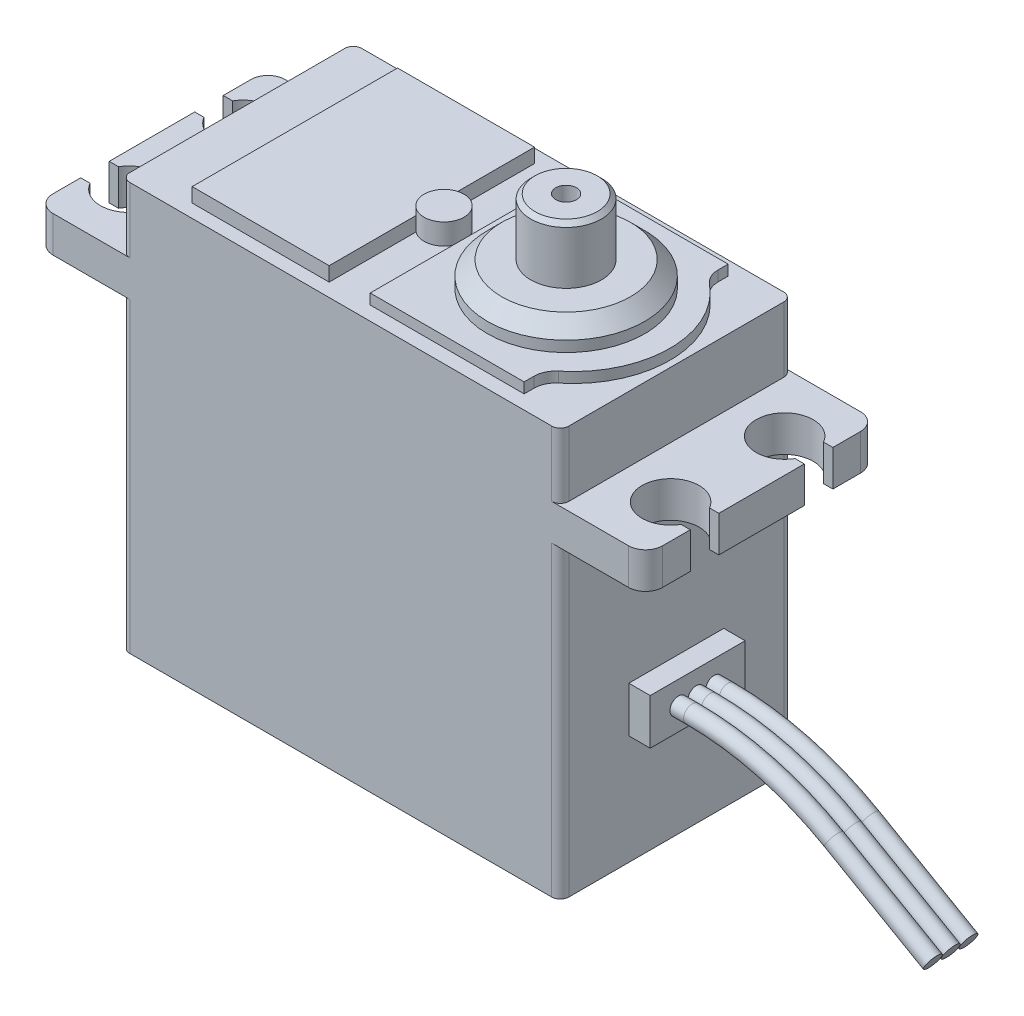
SolidWorks part; units mm, degrees
ref_plane "Front Plane" through (0, 0, 0) normal (0, 0, 1) x (1, 0, 0)
ref_plane "Top Plane" through (0, 0, 0) normal (0, 1, 0) x (1, 0, 0)
ref_plane "Right Plane" through (0, 0, 0) normal (1, 0, 0) x (0, 0, -1)
sketch "Sketch1" plane through (0, 0, 0) normal (0, 1, 0) x (1, 0, 0)
  line L1 (0, 0) -> (30.8, 0)
  line L2 (0, 0) -> (0, 16.28)
  line L3 (0, 16.28) -> (30.8, 16.28)
  line L4 (30.8, 0) -> (30.8, 16.28)
  dimension "D1" = 16.28
  dimension "D2" = 30.8
extrude "Boss-Extrude1" add sketch "Sketch1" along normal blind 28.62
sketch "Sketch3" plane through (0, 0, 0) normal (0, 0, 1) x (1, 0, 0)
  line L0 (0, 21.51) -> (30.8, 21.51) construction
  line L1 (0, 28.62) -> (0, 0) construction
  line L2 (30.8, 28.62) -> (30.8, 0) construction
  line L3 (0, 0) -> (30.8, 0) construction
  line L4 (15.4, 28.62) -> (15.4, 24.7543) construction
  line L5 (30.8, 21.51) -> (36.785, 21.51)
  line L6 (30.8, 21.51) -> (30.8, 24.04)
  line L7 (30.8, 24.04) -> (36.785, 24.04)
  line L8 (36.785, 21.51) -> (36.785, 24.04)
  line L9 (0, 28.62) -> (30.8, 28.62) construction
  line L10 (-5.985, 21.51) -> (-5.985, 24.04)
  line L11 (0, 24.04) -> (-5.985, 24.04)
  line L12 (0, 21.51) -> (0, 24.04)
  line L13 (0, 21.51) -> (-5.985, 21.51)
  dimension "D1" = 21.51
  dimension "D2" = 2.53
  dimension "D3" = 21.385
extrude "Boss-Extrude2" add sketch "Sketch3" against normal up to surface (16.28 mm away) up to face at (15.4, 14.31, -16.28)
sketch "Sketch4" plane through (0, 28.62, 0) normal (0, 1, 0) x (1, 0, 0)
  line L0 (4.04, 8.14) -> (0, 8.14) construction
  line L1 (13.65, 15.345) -> (4.04, 15.345)
  line L2 (13.65, 15.345) -> (13.65, 0.935)
  line L3 (13.65, 0.935) -> (4.04, 0.935)
  line L4 (4.04, 15.345) -> (4.04, 0.935)
  line L5 (0, 16.28) -> (0, 0) construction
  line L6 (30.8, 0) -> (30.8, 16.28) construction
  dimension "D1" = 14.41
  dimension "D2" = 9.61
  dimension "D3" = 26.76
extrude "Boss-Extrude3" add sketch "Sketch4" along normal blind 1
sketch "Sketch5" plane through (0, 28.62, 0) normal (0, 1, 0) x (1, 0, 0)
  line L0 (13.65, 0.935) -> (13.65, 15.345) construction
  line L1 (27.28, 0.985) -> (16.48, 0.985)
  line L2 (27.28, 2.4415) -> (27.28, 13.8385) construction
  line L3 (27.28, 15.295) -> (16.48, 15.295)
  line L4 (16.48, 0.985) -> (16.48, 15.295)
  line L5 (30.36, 8.14) -> (30.8, 8.14) construction
  line L6 (30.8, 0) -> (30.8, 16.28) construction
  line L7 (23.23, 8.14) -> (28.73, 8.14) construction
  line L8 (27.28, 0.985) -> (27.28, 2.4415)
  line L9 (4.04, 15.345) -> (4.04, 0.935) construction
  line L11 (27.28, 13.8385) -> (27.28, 15.295)
  arc A1 (27.28, 2.4415) -> (27.28, 13.8385) centre (23.5484, 8.14) ccw
  dimension "D1" = 2.83
  dimension "D2" = 1.4565
  dimension "D3" = 10.8
  dimension "D5" = 13.88
  dimension "D6" = 24.69
extrude "Boss-Extrude4" add sketch "Sketch5" along normal blind 0.73
sketch "Sketch6" plane through (0, 29.35, 0) normal (0, 1, 0) x (1, 0, 0)
  line L0 (28.59, 8.14) -> (23.07, 8.14) construction
  line L1 (4.04, 15.345) -> (4.04, 0.935) construction
  circle A0 centre (23.07, 8.14) radius 5.52
  dimension "D1" = 11.04
  dimension "D2" = 24.55
extrude "Boss-Extrude5" add sketch "Sketch6" along normal blind 1.75
chamfer "Chamfer1" distance 1 angle 45 1 edges at (23.07, 31.1, -2.62)
fillet "Fillet1" radius 1.5 2 edges at (27.28, 28.985, -13.8385) (27.28, 28.985, -2.4415)
sketch "Sketch7" plane through (0, 28.62, 0) normal (0, 1, 0) x (1, 0, 0)
  circle A0 centre (14.5043, 8.14) radius 1.4
  dimension "D1" = 2.8
extrude "Boss-Extrude6" add sketch "Sketch7" along normal blind 1.47
sketch "Sketch8" plane through (0, 31.1, 0) normal (0, 1, 0) x (1, 0, 0)
  circle A0 centre (23.07, 8.14) radius 2.48
  dimension "D1" = 4.96
extrude "Boss-Extrude7" add sketch "Sketch8" along normal blind 4
sketch "Sketch9" plane through (0, 24.04, 0) normal (0, 1, 0) x (1, 0, 0)
  line L0 (30.8, 8.14) -> (36.785, 8.14) construction
  line L1 (30.8, 16.28) -> (30.8, 0) construction
  line L2 (36.785, 16.28) -> (36.785, 0) construction
  line L3 (15.4, 16.28) -> (15.4, 0) construction
  line L4 (30.8, 16.28) -> (0, 16.28) construction
  line L5 (0, 0) -> (30.8, 0) construction
  line L6 (34.4, 12.14) -> (32.4, 12.14) construction
  line L7 (34.4, 10.14) -> (34.4, 8.14) construction
  line L8 (37.2465, 13.14) -> (37.2465, 11.14)
  line L9 (36.1321, 11.14) -> (37.2465, 11.14)
  line L10 (36.1321, 3.14) -> (37.2465, 3.14)
  line L11 (36.1321, 13.14) -> (37.2465, 13.14)
  line L12 (37.2465, 3.14) -> (37.2465, 5.14)
  line L13 (36.1321, 5.14) -> (37.2465, 5.14)
  line L14 (-3.6, 10.14) -> (-3.6, 8.14) construction
  line L15 (-3.6, 12.14) -> (-1.6, 12.14) construction
  line L16 (0, 8.14) -> (-5.985, 8.14) construction
  line L17 (-5.3321, 5.14) -> (-6.4465, 5.14)
  line L18 (-6.4465, 3.14) -> (-6.4465, 5.14)
  line L19 (-5.3321, 13.14) -> (-6.4465, 13.14)
  line L20 (-5.3321, 3.14) -> (-6.4465, 3.14)
  line L21 (-5.3321, 11.14) -> (-6.4465, 11.14)
  line L22 (-6.4465, 13.14) -> (-6.4465, 11.14)
  arc A0 (36.1321, 13.14) -> (36.1321, 11.14) centre (34.4, 12.14) ccw
  arc A1 (36.1321, 3.14) -> (36.1321, 5.14) centre (34.4, 4.14) cw
  arc A2 (-5.3321, 3.14) -> (-5.3321, 5.14) centre (-3.6, 4.14) ccw
  arc A3 (-5.3321, 13.14) -> (-5.3321, 11.14) centre (-3.6, 12.14) cw
  point P17 (36.4, 12.14)
  point P41 (-5.6, 12.14)
  dimension "D1" = 4
  dimension "D2" = 17
  dimension "D3" = 2
  dimension "D4" = 2
extrude "Cut-Extrude1" cut sketch "Sketch9" against normal blind 4
sketch "Sketch10" plane through (30.8, 0, 0) normal (1, 0, 0) x (0, 0, -1)
  line L0 (8.14, 7.69) -> (8.14, 0) construction
  line L1 (4.81, 7.69) -> (11.47, 7.69)
  line L2 (4.81, 7.69) -> (4.81, 10.89)
  line L3 (4.81, 10.89) -> (11.47, 10.89)
  line L4 (11.47, 7.69) -> (11.47, 10.89)
  line L5 (4.81, 7.69) -> (11.47, 10.89) construction
  line L6 (4.81, 10.89) -> (11.47, 7.69) construction
  line L7 (0, 0) -> (16.28, 0) construction
  point P0 (8.14, 9.29)
  dimension "D1" = 6.66
  dimension "D2" = 3.2
  dimension "D3" = 7.69
extrude "Boss-Extrude8" add sketch "Sketch10" along normal blind 1.5
sketch "Sketch11" plane through (32.3, 0, 0) normal (1, 0, 0) x (0, 0, -1)
  circle A0 centre (6.794, 9.2745) radius 0.6
  circle A1 centre (8.0453, 9.2745) radius 0.6
  circle A2 centre (9.29, 9.2745) radius 0.6
  dimension "D1" = 1.2
ref_plane "Plane1" through (0, 0, -8.14) normal (0, 0, -1) x (-1, 0, 0)
sketch "Sketch12" plane through (0, 0, -8.14) normal (0, 0, -1) x (-1, 0, 0)
  line L0 (-32.3, 9.2745) -> (-33.2613, 9.2745)
  line L1 (-32.3, 9.8745) -> (-32.3, 8.6745) construction
  line L2 (-43.2074, 6.626) -> (-50.1464, 2.6485)
  arc A1 (-33.2613, 9.2745) -> (-43.2074, 6.626) centre (-33.2613, -10.7255) ccw
sweep "Sweep1" add profiles "Sketch11" path "Sketch12"
fillet "Fillet2" radius 1.2 4 edges at (-5.985, 22.775, 0) (-5.985, 22.775, -16.28) (36.785, 22.775, 0) (36.785, 22.775, -16.28)
fillet "Fillet3" radius 0.6 8 edges
chamfer "Chamfer2" distance 0.3 angle 45 1 edges at (23.07, 35.1, -5.66)
sketch "Sketch13" plane through (0, 35.1, 0) normal (0, 1, 0) x (1, 0, 0)
  circle A0 centre (23.07, 8.14) radius 0.7264
extrude "Cut-Extrude2" cut sketch "Sketch13" against normal blind 2.5
sketch "Sketch14" plane through (0, 0, -16.28) normal (0, 0, -1) x (-1, 0, 0)
  text T0 "Daniel Angeles" font "Lemon/Milk" height in points 8
